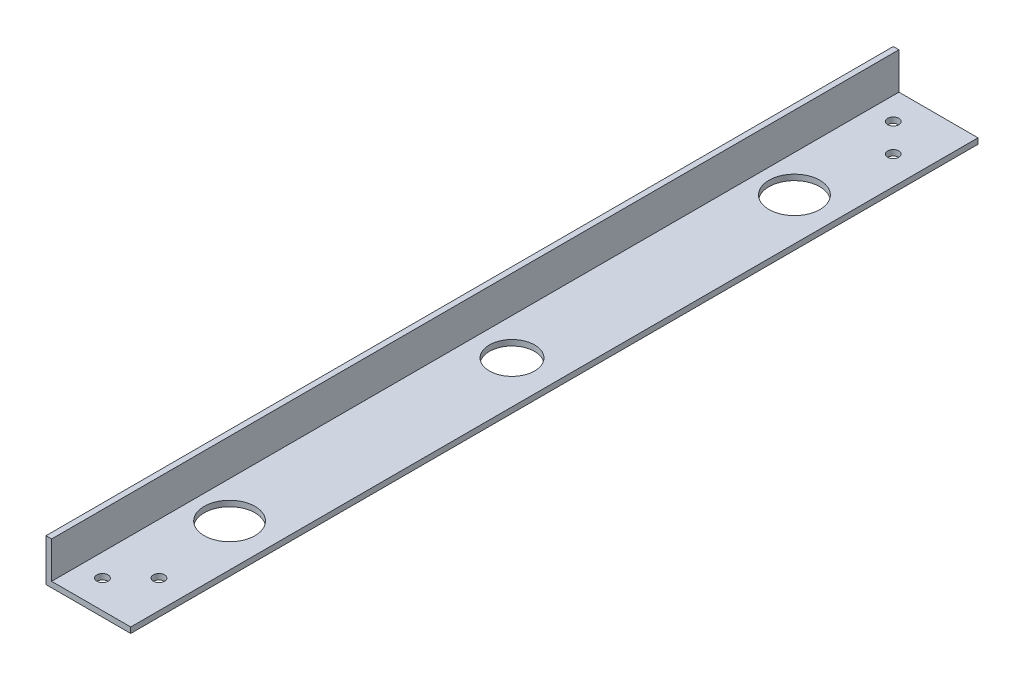
SolidWorks part; units mm, degrees
ref_plane "Front Plane" through (0, 0, 0) normal (0, 0, 1) x (1, 0, 0)
ref_plane "Top Plane" through (0, 0, 0) normal (0, 1, 0) x (1, 0, 0)
ref_plane "Right Plane" through (0, 0, 0) normal (1, 0, 0) x (0, 0, -1)
sketch "Sketch1" plane through (0, 0, 0) normal (0, 0, 1) x (1, 0, 0)
  line L0 (0, 0) -> (0, 25)
  line L1 (0, 25) -> (2, 25)
  line L2 (2, 25) -> (2, 2)
  line L3 (2, 2) -> (30, 2)
  line L4 (30, 2) -> (30, 0)
  line L5 (30, 0) -> (0, 0)
  dimension "D1" = 2
  dimension "D2" = 25
  dimension "D3" = 30
extrude "Boss-Extrude1" add sketch "Sketch1" along normal blind 300
sketch "Sketch2" plane through (0, 2, 0) normal (0, 1, 0) x (1, 0, 0)
  line L0 (30, -150) -> (2, -150) construction
  line L1 (30, -300) -> (30, 0) construction
  line L2 (2, -300) -> (2, 0) construction
  line L3 (30, -10) -> (2, -10) construction
  line L4 (30, -20) -> (2, -20) construction
  line L5 (30, -290) -> (2, -290) construction
  line L6 (30, -280) -> (2, -280) construction
  line L7 (30, -300) -> (2, -300) construction
  line L8 (30, 0) -> (2, 0) construction
  line L9 (10, -290) -> (10, -10) construction
  line L10 (20, -20) -> (20, -280) construction
  circle A0 centre (15, -150) radius 8
  circle A1 centre (10, -10) radius 1.9777
  circle A2 centre (20, -20) radius 1.9777
  circle A3 centre (10, -290) radius 1.9777
  circle A4 centre (20, -280) radius 1.9777
  dimension "D2" = 16
  dimension "D1" = 15
  dimension "D3" = 10
  dimension "D4" = 20
  dimension "D5" = 20
  dimension "D6" = 10
  dimension "D7" = 10
  dimension "D8" = 20
extrude "Cut-Extrude1" cut sketch "Sketch2" against normal blind 10
sketch "Sketch3" plane through (2, 0, 0) normal (1, 0, 0) x (0, 0, -1)
  line L8 (0, 2) -> (0, 25) construction
  line L9 (-300, 25) -> (0, 25)
  line L13 (-300, 25) -> (-300, 15)
  line L14 (-300, 15) -> (0, 15)
  line L15 (0, 25) -> (0, 15)
  dimension "D5" = 15
extrude "Cut-Extrude2" cut sketch "Sketch3" against normal blind 10
sketch "Sketch6" plane through (0, 0, 0) normal (0, -1, 0) x (1, 0, 0)
  circle A0 centre (15, 250) radius 9
  circle A1 centre (15, 50) radius 9
  circle A2 centre (-238, 50) radius 9
  circle A3 centre (-238, 250) radius 9
extrude "Cut-Extrude5" cut sketch "Sketch6" against normal blind 5
